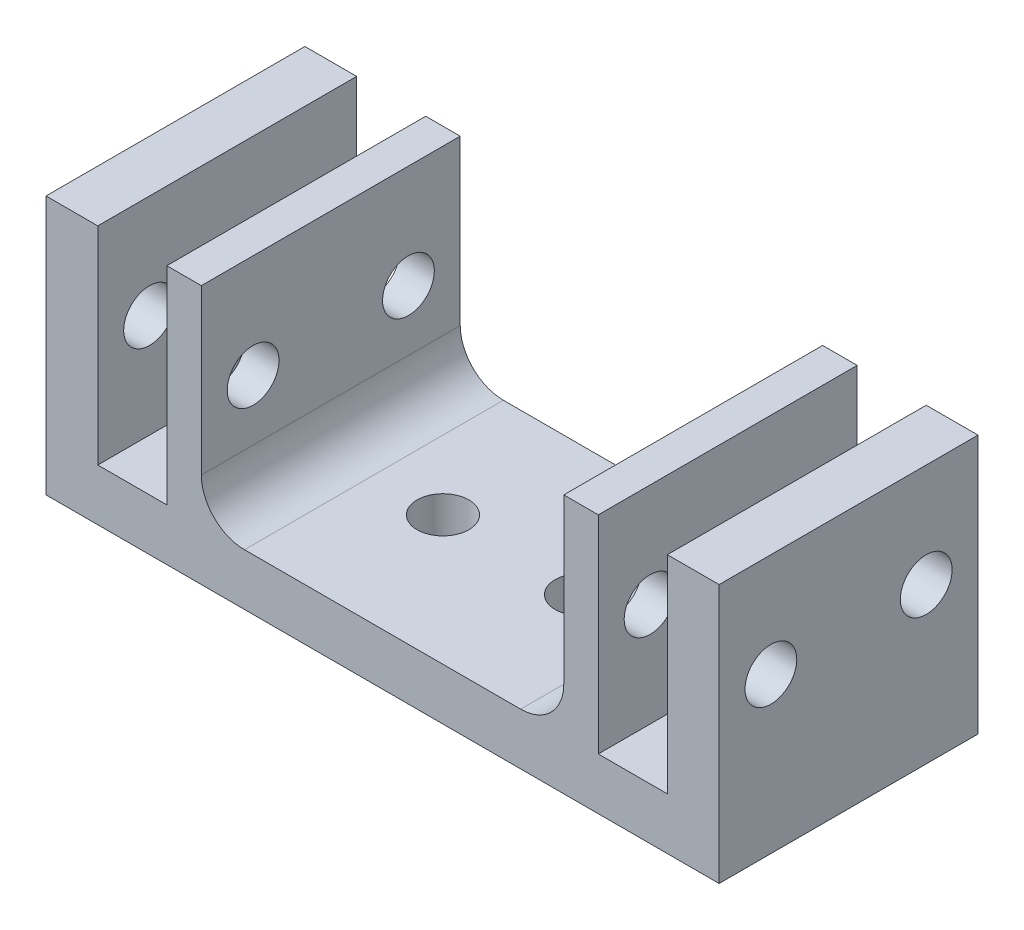
SolidWorks part; units mm, degrees
material "POM 乙缩醛共聚物"
ref_plane "前视基准面" through (0, 0, 0) normal (0, 0, 1) x (1, 0, 0)
ref_plane "上视基准面" through (0, 0, 0) normal (0, 1, 0) x (1, 0, 0)
ref_plane "右视基准面" through (0, 0, 0) normal (1, 0, 0) x (0, 0, -1)
sketch "草图1" plane through (0, 0, 0) normal (0, 0, 1) x (1, 0, 0)
  line L0 (0, 0) -> (0, 8.0938) construction
  line L1 (19.5, 0) -> (-19.5, 0)
  line L2 (-19.5, 0) -> (-19.5, 15)
  line L3 (19.5, 0) -> (19.5, 15)
  line L4 (-19.5, 15) -> (-16.5, 15)
  line L5 (19.5, 15) -> (16.5, 15)
  line L6 (-16.5, 15) -> (-16.5, 3)
  line L7 (16.5, 15) -> (16.5, 3)
  line L8 (-16.5, 3) -> (-12.5, 3)
  line L9 (16.5, 3) -> (12.5, 3)
  line L10 (-12.5, 3) -> (-12.5, 15)
  line L11 (12.5, 3) -> (12.5, 15)
  line L12 (-12.5, 15) -> (-10.5, 15)
  line L13 (12.5, 15) -> (10.5, 15)
  line L14 (-10.5, 15) -> (-10.5, 3)
  line L15 (10.5, 15) -> (10.5, 3)
  line L16 (-10.5, 3) -> (10.5, 3)
  point P20 (0, 3)
  dimension "D1" = 39
  dimension "D2" = 2
  dimension "D3" = 3
  dimension "D4" = 15
  dimension "D5" = 4
  dimension "D6" = 3
extrude "凸台-拉伸1" add sketch "草图1" along normal blind 15
sketch "草图2" plane through (0, 3, 0) normal (0, 1, 0) x (1, 0, 0)
  line L0 (-10.5, -7.5) -> (10.5, -7.5) construction
  line L1 (-10.5, -15) -> (-10.5, 0) construction
  line L2 (10.5, -15) -> (10.5, 0) construction
  line L3 (0, -7.5) -> (0, 0) construction
  circle A0 centre (-4, -7.5) radius 1.5
  circle A1 centre (4, -7.5) radius 1.5
  dimension "D1" = 4
  dimension "D2" = 3
extrude "切除-拉伸1" cut sketch "草图2" against normal blind 15
sketch "草图3" plane through (19.5, 0, 0) normal (1, 0, 0) x (0, 0, -1)
  line L0 (-15, 9) -> (0, 9) construction
  line L1 (-15, 0) -> (-15, 15) construction
  line L2 (0, 0) -> (0, 15) construction
  line L3 (-15, 15) -> (0, 15) construction
  line L4 (-7.5, 15) -> (-7.5, 9) construction
  circle A0 centre (-12, 9) radius 1.5
  circle A1 centre (-3, 9) radius 1.5
  dimension "D2" = 3
  dimension "D1" = 6
  dimension "D3" = 4.5
extrude "切除-拉伸2" cut sketch "草图3" against normal through all
fillet "圆角1" radius 2.5 2 edges at (10.5, 3, 7.5) (-10.5, 3, 7.5)
